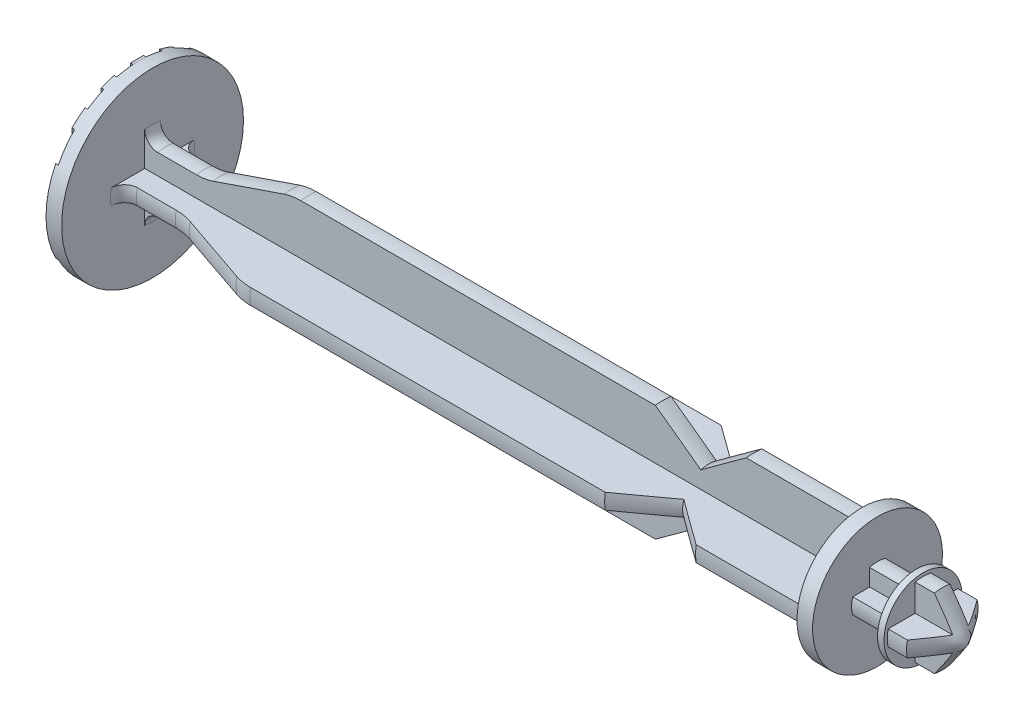
SolidWorks part; units mm, degrees
material "Polyethylene Cross-Linked"
ref_plane "Front Plane" through (0, 0, 0) normal (0, 0, 1) x (1, 0, 0)
ref_plane "Top Plane" through (0, 0, 0) normal (0, 1, 0) x (1, 0, 0)
ref_plane "Right Plane" through (0, 0, 0) normal (1, 0, 0) x (0, 0, -1)
sketch "Sketch1" plane through (0, 0, 0) normal (0, 0, 1) x (1, 0, 0)
  line L0 (64, 0) -> (-64, 0) construction
  line L1 (0, 0) -> (0, 7)
  line L2 (0, 7) -> (1.2, 7)
  line L3 (1.2, 7) -> (1.2, 3.25)
  line L4 (2.2, 2.25) -> (5.2, 2.25)
  line L5 (6.475, 2.4586) -> (11.925, 4.2914)
  line L6 (13.2, 4.5) -> (40.5, 4.5)
  line L7 (40.5, 4.5) -> (44, 2)
  line L8 (44, 2) -> (47.5, 4.5)
  line L9 (47.5, 4.5) -> (55.8, 4.5)
  line L10 (55.8, 4.5) -> (55.8, 5)
  line L11 (55.8, 5) -> (57, 5)
  line L12 (57, 5) -> (57, 2)
  line L13 (57, 2) -> (60, 2)
  line L14 (60, 2) -> (60, 3)
  line L15 (60, 3) -> (61.8, 3)
  line L16 (61.8, 3) -> (64, 0)
  line L17 (0, 0) -> (64, 0)
  arc A0 (1.2, 3.25) -> (2.2, 2.25) centre (2.2, 3.25) ccw
  arc A1 (11.925, 4.2914) -> (13.2, 4.5) centre (13.2, 0.5) cw
  arc A2 (5.2, 2.25) -> (6.475, 2.4586) centre (5.2, 6.25) ccw
  point P4 (0, 0)
  dimension "D14" = 1
  dimension "D15" = 4
  dimension "D1" = 1.2
  dimension "D2" = 7
  dimension "D3" = 14
  dimension "D4" = 4.5
  dimension "D5" = 64
  dimension "D6" = 4
  dimension "D7" = 7
  dimension "D8" = 9
  dimension "D9" = 10
  dimension "D10" = 4
  dimension "D11" = 6
  dimension "D12" = 20
  dimension "D13" = 4
  dimension "D16" = 4
  dimension "D17" = 12
  dimension "D18" = 2.2
  dimension "D19" = 126.254
revolve "Revolve1" add sketch "Sketch1" angle 360 about L0
sketch "Sketch2" plane through (1.2, 0, 0) normal (1, 0, 0) x (0, 0, -1)
  line L0 (17.7295, 0) -> (-17.7295, 0) construction
  line L1 (0, -17.5817) -> (0, 17.5817) construction
  line L2 (-0.6, 6.9742) -> (-0.6, 0.6)
  line L3 (-0.6, 0.6) -> (-6.9742, 0.6)
  line L4 (0.6, 0.6) -> (0.6, 6.9742)
  line L5 (6.9742, 0.6) -> (0.6, 0.6)
  line L6 (0.6, -0.6) -> (6.9742, -0.6)
  line L7 (0.6, -6.9742) -> (0.6, -0.6)
  line L8 (-0.6, -0.6) -> (-0.6, -6.9742)
  line L9 (-6.9742, -0.6) -> (-0.6, -0.6)
  circle A0 centre (0, 0) radius 7 construction
  arc A1 (-6.9742, 0.6) -> (-6.9742, -0.6) centre (0, 0) ccw
  arc A2 (0.6, 6.9742) -> (-0.6, 6.9742) centre (0, 0) ccw
  arc A3 (6.9742, -0.6) -> (6.9742, 0.6) centre (0, 0) ccw
  arc A4 (-0.6, -6.9742) -> (0.6, -6.9742) centre (0, 0) ccw
  point P5 (0, 0)
  point P9 (0, 0)
  point P27 (0, 0)
  dimension "D3" = 1.2
  dimension "D2" = 4
extrude "Cut-Extrude1" cut sketch "Sketch2" along normal up to surface (54.6 mm away) flip side to cut up to face at (55.8, 0, -4.5)
sketch "Sketch3" plane through (0, 0, 0) normal (-1, 0, 0) x (0, 0, 1)
  line L0 (2.75, -6.9821) -> (1.75, -6.9821)
  line L1 (0.5, -6.9821) -> (-0.5, -6.9821)
  line L2 (0.5, -6.9821) -> (0.5, 6.9821)
  line L3 (0.5, 6.9821) -> (-0.5, 6.9821)
  line L4 (-0.5, -6.9821) -> (-0.5, 6.9821)
  line L5 (0.5, -6.9821) -> (-0.5, 6.9821) construction
  line L6 (0.5, 6.9821) -> (-0.5, -6.9821) construction
  line L7 (1.75, -6.9821) -> (1.75, 6.9821)
  line L8 (2.75, 6.9821) -> (1.75, 6.9821)
  line L9 (2.75, -6.9821) -> (2.75, 6.9821)
  line L10 (5, -6.9821) -> (4, -6.9821)
  line L11 (4, -6.9821) -> (4, 6.9821)
  line L12 (5, 6.9821) -> (4, 6.9821)
  line L13 (5, -6.9821) -> (5, 6.9821)
  line L14 (7.25, -6.9821) -> (6.25, -6.9821)
  line L15 (6.25, -6.9821) -> (6.25, 6.9821)
  line L16 (7.25, 6.9821) -> (6.25, 6.9821)
  line L17 (7.25, -6.9821) -> (7.25, 6.9821)
  line L18 (9.5, -6.9821) -> (8.5, -6.9821)
  line L19 (8.5, -6.9821) -> (8.5, 6.9821)
  line L20 (9.5, 6.9821) -> (8.5, 6.9821)
  line L21 (9.5, -6.9821) -> (9.5, 6.9821)
  line L22 (11.75, -6.9821) -> (10.75, -6.9821)
  line L23 (10.75, -6.9821) -> (10.75, 6.9821)
  line L24 (11.75, 6.9821) -> (10.75, 6.9821)
  line L25 (11.75, -6.9821) -> (11.75, 6.9821)
  line L26 (14, -6.9821) -> (13, -6.9821)
  line L27 (13, -6.9821) -> (13, 6.9821)
  line L28 (14, 6.9821) -> (13, 6.9821)
  line L29 (14, -6.9821) -> (14, 6.9821)
  line L30 (-1.75, -6.9821) -> (-2.75, -6.9821)
  line L31 (-2.75, -6.9821) -> (-2.75, 6.9821)
  line L32 (-1.75, 6.9821) -> (-2.75, 6.9821)
  line L33 (-1.75, -6.9821) -> (-1.75, 6.9821)
  line L34 (-4, -6.9821) -> (-5, -6.9821)
  line L35 (-5, -6.9821) -> (-5, 6.9821)
  line L36 (-4, 6.9821) -> (-5, 6.9821)
  line L37 (-4, -6.9821) -> (-4, 6.9821)
  line L38 (-6.25, -6.9821) -> (-7.25, -6.9821)
  line L39 (-7.25, -6.9821) -> (-7.25, 6.9821)
  line L40 (-6.25, 6.9821) -> (-7.25, 6.9821)
  line L41 (-6.25, -6.9821) -> (-6.25, 6.9821)
  line L42 (-8.5, -6.9821) -> (-9.5, -6.9821)
  line L43 (-9.5, -6.9821) -> (-9.5, 6.9821)
  line L44 (-8.5, 6.9821) -> (-9.5, 6.9821)
  line L45 (-8.5, -6.9821) -> (-8.5, 6.9821)
  line L46 (-10.75, -6.9821) -> (-11.75, -6.9821)
  line L47 (-11.75, -6.9821) -> (-11.75, 6.9821)
  line L48 (-10.75, 6.9821) -> (-11.75, 6.9821)
  line L49 (-10.75, -6.9821) -> (-10.75, 6.9821)
  line L50 (-13, -6.9821) -> (-14, -6.9821)
  line L51 (-14, -6.9821) -> (-14, 6.9821)
  line L52 (-13, 6.9821) -> (-14, 6.9821)
  line L53 (-13, -6.9821) -> (-13, 6.9821)
  circle A0 centre (0, 0) radius 7 construction
  point P0 (0, 0)
  dimension "D1" = 1
  dimension "D3" = 2.25
  dimension "D2" = 7
  dimension "D4" = 7
extrude "Cut-Extrude2" cut sketch "Sketch3" against normal blind 0.2 flip side to cut
sketch "Sketch4" plane through (57, 0, 0) normal (1, 0, 0) x (0, 0, -1)
  line L8 (0.6, 0.6) -> (0.6, 6.9742)
  line L9 (-0.6, 6.9742) -> (-0.6, 0.6)
  line L10 (-0.6, 0.6) -> (-6.9742, 0.6)
  line L11 (-6.9742, -0.6) -> (-0.6, -0.6)
  line L12 (-0.6, -0.6) -> (-0.6, -6.9742)
  line L13 (0.6, -6.9742) -> (0.6, -0.6)
  line L14 (0.6, -0.6) -> (6.9742, -0.6)
  line L15 (6.9742, 0.6) -> (0.6, 0.6)
  line L16 (0.6, 0.6) -> (0.6, 6.9742)
  line L17 (-0.6, 6.9742) -> (-0.6, 0.6)
  line L18 (-0.6, 0.6) -> (-6.9742, 0.6)
  line L19 (-6.9742, -0.6) -> (-0.6, -0.6)
  line L20 (-0.6, -0.6) -> (-0.6, -6.9742)
  line L21 (0.6, -6.9742) -> (0.6, -0.6)
  line L22 (0.6, -0.6) -> (6.9742, -0.6)
  line L23 (6.9742, 0.6) -> (0.6, 0.6)
  arc A4 (0.6, 6.9742) -> (-0.6, 6.9742) centre (0, 0) ccw
  arc A5 (-6.9742, 0.6) -> (-6.9742, -0.6) centre (0, 0) ccw
  arc A6 (-0.6, -6.9742) -> (0.6, -6.9742) centre (0, 0) ccw
  arc A7 (6.9742, -0.6) -> (6.9742, 0.6) centre (0, 0) ccw
  arc A8 (0.6, 6.9742) -> (-0.6, 6.9742) centre (0, 0) ccw
  arc A9 (-6.9742, 0.6) -> (-6.9742, -0.6) centre (0, 0) ccw
  arc A10 (-0.6, -6.9742) -> (0.6, -6.9742) centre (0, 0) ccw
  arc A11 (6.9742, -0.6) -> (6.9742, 0.6) centre (0, 0) ccw
  dimension "D1" = 0
extrude "Cut-Extrude3" cut sketch "Sketch4" along normal up to surface (3 mm away) flip side to cut up to face at (60, 0, -2)
ref_plane "Plane1" through (64, 0, 0) normal (1, 0, 0) x (0, 0, -1)
sketch "Sketch5" plane through (64, 0, 0) normal (1, 0, 0) x (0, 0, -1)
  line L8 (0.6, 0.6) -> (0.6, 6.9742)
  line L9 (-0.6, 6.9742) -> (-0.6, 0.6)
  line L10 (-0.6, 0.6) -> (-6.9742, 0.6)
  line L11 (-6.9742, -0.6) -> (-0.6, -0.6)
  line L12 (-0.6, -0.6) -> (-0.6, -6.9742)
  line L13 (0.6, -6.9742) -> (0.6, -0.6)
  line L14 (0.6, -0.6) -> (6.9742, -0.6)
  line L15 (6.9742, 0.6) -> (0.6, 0.6)
  line L16 (0.6, 0.6) -> (0.6, 2.6837)
  line L17 (-0.6, 2.6837) -> (-0.6, 0.6)
  line L18 (-0.6, 0.6) -> (-2.6837, 0.6)
  line L19 (-2.6837, -0.6) -> (-0.6, -0.6)
  line L20 (-0.6, -0.6) -> (-0.6, -2.6837)
  line L21 (0.6, -2.6837) -> (0.6, -0.6)
  line L22 (0.6, -0.6) -> (2.6837, -0.6)
  line L23 (2.6837, 0.6) -> (0.6, 0.6)
  arc A0 (-2.6837, 0.6) -> (-2.6837, -0.6) centre (0, 0) ccw
  arc A1 (2.6837, -0.6) -> (2.6837, 0.6) centre (0, 0) ccw
  arc A2 (0.6, 2.6837) -> (-0.6, 2.6837) centre (0, 0) ccw
  arc A3 (-0.6, -2.6837) -> (0.6, -2.6837) centre (0, 0) ccw
  arc A4 (0.6, 6.9742) -> (-0.6, 6.9742) centre (0, 0) ccw
  arc A5 (-6.9742, 0.6) -> (-6.9742, -0.6) centre (0, 0) ccw
  arc A6 (-0.6, -6.9742) -> (0.6, -6.9742) centre (0, 0) ccw
  arc A7 (6.9742, -0.6) -> (6.9742, 0.6) centre (0, 0) ccw
  dimension "D2" = 5.5
  dimension "D1" = 0
extrude "Cut-Extrude4" cut sketch "Sketch5" against normal blind 3.5 flip side to cut
